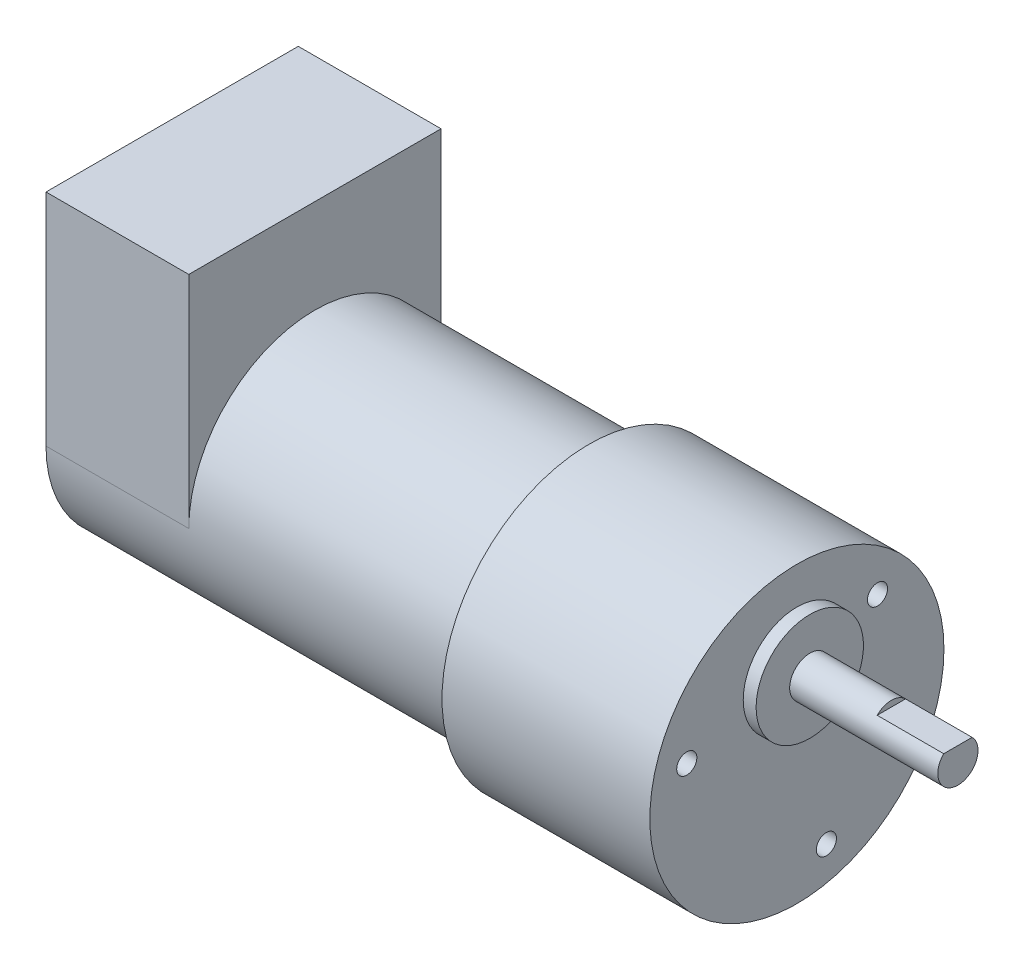
SolidWorks part; units mm, degrees
ref_plane "Front Plane" through (0, 0, 0) normal (0, 0, 1) x (1, 0, 0)
ref_plane "Top Plane" through (0, 0, 0) normal (0, 1, 0) x (1, 0, 0)
ref_plane "Right Plane" through (0, 0, 0) normal (1, 0, 0) x (0, 0, -1)
sketch "Sketch1" plane through (0, 0, 0) normal (1, 0, 0) x (0, 0, -1)
  circle A0 centre (0, 0) radius 14.9225
  dimension "D1" = 29.845
extrude "Boss-Extrude1" add sketch "Sketch1" along normal blind 49.3268
sketch "Sketch2" plane through (0, 0, 0) normal (-1, 0, 0) x (0, 0, 1)
  line L0 (-14.9225, 0) -> (-14.9225, 52.1023) construction
  line L1 (14.9225, 0) -> (14.9225, 52.8903) construction
  line L2 (-14.9225, 26.035) -> (14.9225, 26.035)
  line L3 (-14.9225, 26.035) -> (-14.9225, 0)
  line L4 (14.9225, 26.035) -> (14.9225, 0)
  circle A0 centre (0, 0) radius 14.9225 construction
  arc A1 (14.9225, 0) -> (-14.9225, 0) centre (0, 0) cw
  dimension "D1" = 26.035
extrude "Boss-Extrude2" add sketch "Sketch2" against normal blind 16.891
sketch "Sketch3" plane through (49.3268, 0, 0) normal (1, 0, 0) x (0, 0, -1)
  circle A0 centre (0, 0) radius 17.399
  dimension "D1" = 34.798
extrude "Boss-Extrude3" add sketch "Sketch3" along normal blind 24.5872
sketch "Sketch4" plane through (73.914, 0, 0) normal (1, 0, 0) x (0, 0, -1)
  line L0 (0, -17.399) -> (0, 17.399) construction
  line L1 (17.399, 0) -> (-17.399, 0) construction
  circle A0 centre (0, 6.6548) radius 2.3787
  circle A1 centre (0, 0) radius 17.399 construction
  dimension "D1" = 4.7574
  dimension "D2" = 6.6548
extrude "Boss-Extrude4" add sketch "Sketch4" along normal blind 19.05
sketch "Sketch5" plane through (73.914, 0, 0) normal (1, 0, 0) x (0, 0, -1)
  circle A0 centre (0, 6.6548) radius 6.35
  dimension "D1" = 12.7
extrude "Boss-Extrude5" add sketch "Sketch5" along normal blind 1.524
sketch "Sketch6" plane through (73.914, 0, 0) normal (1, 0, 0) x (0, 0, -1)
  line L0 (0, 0) -> (0, -17.399) construction
  line L1 (0, 0) -> (3.4908, -13.0278) construction
  circle A0 centre (0, 0) radius 13.4874 construction
  circle A1 centre (3.4908, -13.0278) radius 1.1906
  circle A2 centre (-13.0278, 3.4908) radius 1.1906
  circle A3 centre (9.537, 9.537) radius 1.1906
  circle A4 centre (0, 0) radius 17.399 construction
  point P12 (0, 0)
  dimension "D1" = 26.9748
  dimension "D2" = 2.3813
  dimension "D4" = 15
  dimension "D3" = 3
extrude "Cut-Extrude1" cut sketch "Sketch6" against normal blind 19.05
sketch "Sketch7" plane through (92.964, 0, 0) normal (1, 0, 0) x (0, 0, -1)
  line L0 (-1.6787, 8.3401) -> (1.6787, 8.3401)
  line L1 (0, 9.0335) -> (0, 4.2761) construction
  circle A0 centre (0, 6.6548) radius 2.3787 construction
  circle A1 centre (0, 6.6548) radius 2.3787 construction
  arc A2 (1.6787, 8.3401) -> (-1.6787, 8.3401) centre (0, 6.6548) ccw
  dimension "D1" = 4.064
extrude "Cut-Extrude2" cut sketch "Sketch7" against normal blind 7.874
